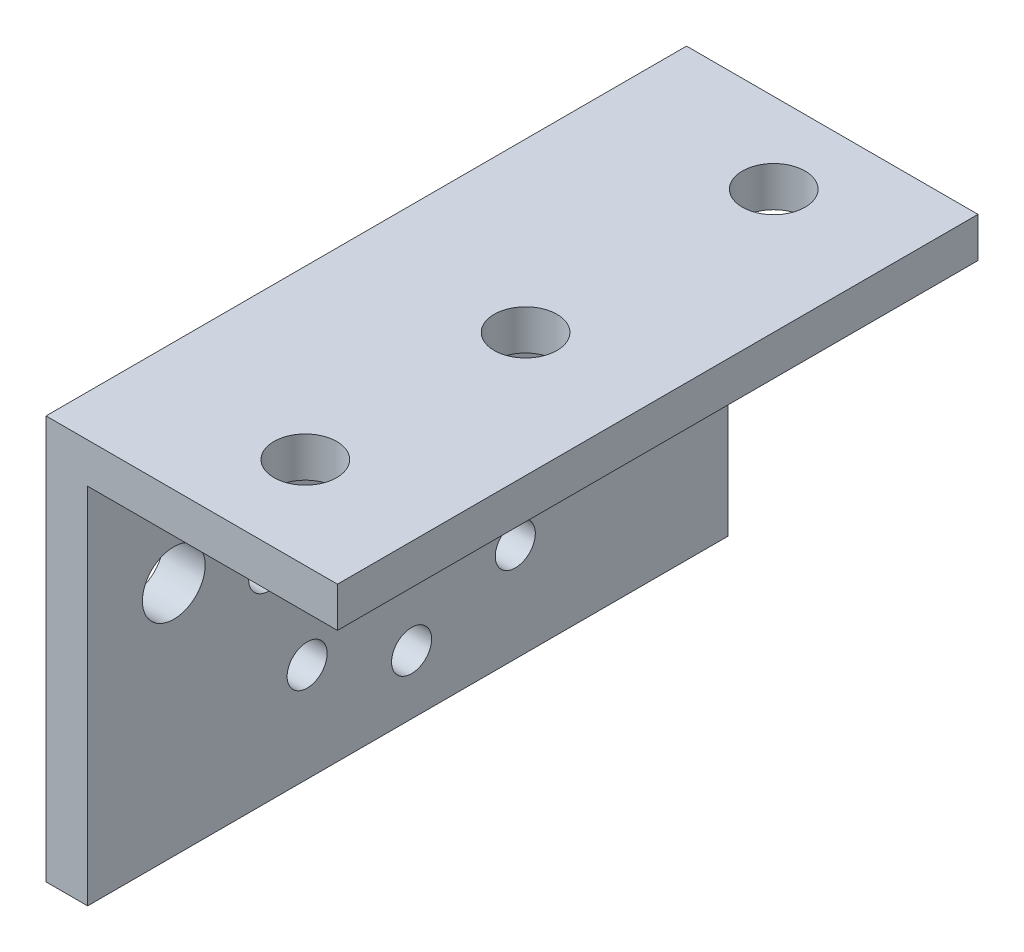
SolidWorks part; units mm, degrees
material "Alumina"
ref_plane "Front Plane" through (0, 0, 0) normal (0, 0, 1) x (1, 0, 0)
ref_plane "Top Plane" through (0, 0, 0) normal (0, 1, 0) x (1, 0, 0)
ref_plane "Right Plane" through (0, 0, 0) normal (1, 0, 0) x (0, 0, -1)
sketch "Sketch1" plane through (0, 0, 0) normal (0, 0, 1) x (1, 0, 0)
  line L0 (0, 0) -> (0, 32.004)
  line L1 (0, 32.004) -> (23.114, 32.004)
  line L2 (23.114, 32.004) -> (23.114, 28.829)
  line L3 (0, 0) -> (3.302, 0)
  line L4 (3.302, 0) -> (3.302, 28.829)
  line L5 (3.302, 28.829) -> (23.114, 28.829)
  dimension "D1" = 32.004
  dimension "D2" = 23.114
  dimension "D3" = 3.175
extrude "Boss-Extrude1" add sketch "Sketch1" along normal blind 50.8
hole_wizard "#9 (0.196) Diameter Hole2" positions "Sketch11" profile "Sketch12" hole size "#9" standard "ANSI Inch" end condition through all
sketch "Sketch11" plane through (0, 32.004, 0) normal (0, 1, 0) x (1, 0, 0)
  point P0 (13.2808, -26.0466)
  point P2 (13.2808, -6.3662)
  point P4 (13.2808, -43.5141)
sketch "Sketch12" plane through (13.2808, 32.004, 26.0466) normal (1, 0, 0) x (0, 0, 1)
  line L0 (0, 0) -> (0, 32.004)
  line L1 (0, 32.004) -> (2.4892, 32.004)
  line L2 (2.4892, 32.004) -> (2.4892, 0)
  line L5 (2.4892, 0) -> (0, 0)
  line L11 (0, -6.35) -> (0, 107.95) construction
  dimension "Thru Hole Dia." = 4.9784
  dimension "Thru Hole Depth" = 32.004
hole_wizard "#9 (0.196) Diameter Hole3" positions "Sketch13" profile "Sketch14" hole size "#9" standard "ANSI Inch" end condition up to next
sketch "Sketch13" plane through (0, 0, 0) normal (-1, 0, 0) x (0, 0, 1)
  point P0 (6.2897, 18.7617)
  point P2 (26.2056, 18.7617)
  point P4 (43.9669, 18.7617)
sketch "Sketch14" plane through (0, 18.7617, 6.2897) normal (0, 1, 0) x (0, 0, 1)
  line L0 (0, 0) -> (0, 3.302)
  line L1 (0, 3.302) -> (2.4892, 3.302)
  line L2 (2.4892, 3.302) -> (2.4892, 0)
  line L5 (2.4892, 0) -> (0, 0)
  line L11 (0, -6.35) -> (0, 107.95) construction
  dimension "Thru Hole Dia." = 4.9784
  dimension "Thru Hole Depth" = 3.302
hole_wizard "1/8 (0.125) Diameter Hole1" positions "Sketch15" profile "Sketch16" hole size "1/8" standard "ANSI Inch"
sketch "Sketch15" plane through (0, 0, 0) normal (-1, 0, 0) x (0, 0, 1)
  point P0 (36.4429, 16.0283)
  point P2 (33.393, 7.8428)
  point P4 (25.1091, 4.6945)
  point P6 (16.8842, 7.8428)
  point P8 (13.7949, 16.0283)
  point P10 (16.8842, 24.2926)
  point P12 (25.1091, 27.3621)
  point P14 (33.393, 24.2926)
sketch "Sketch16" plane through (0, 16.0283, 36.4429) normal (0, 1, 0) x (0, 0, 1)
  line L0 (0, 0) -> (0, 3.302)
  line L1 (0, 3.302) -> (1.5875, 3.302)
  line L2 (1.5875, 3.302) -> (1.5875, 0)
  line L5 (1.5875, 0) -> (0, 0)
  line L11 (0, -6.35) -> (0, 107.95) construction
  dimension "Thru Hole Dia." = 3.175
  dimension "Thru Hole Depth" = 3.302
